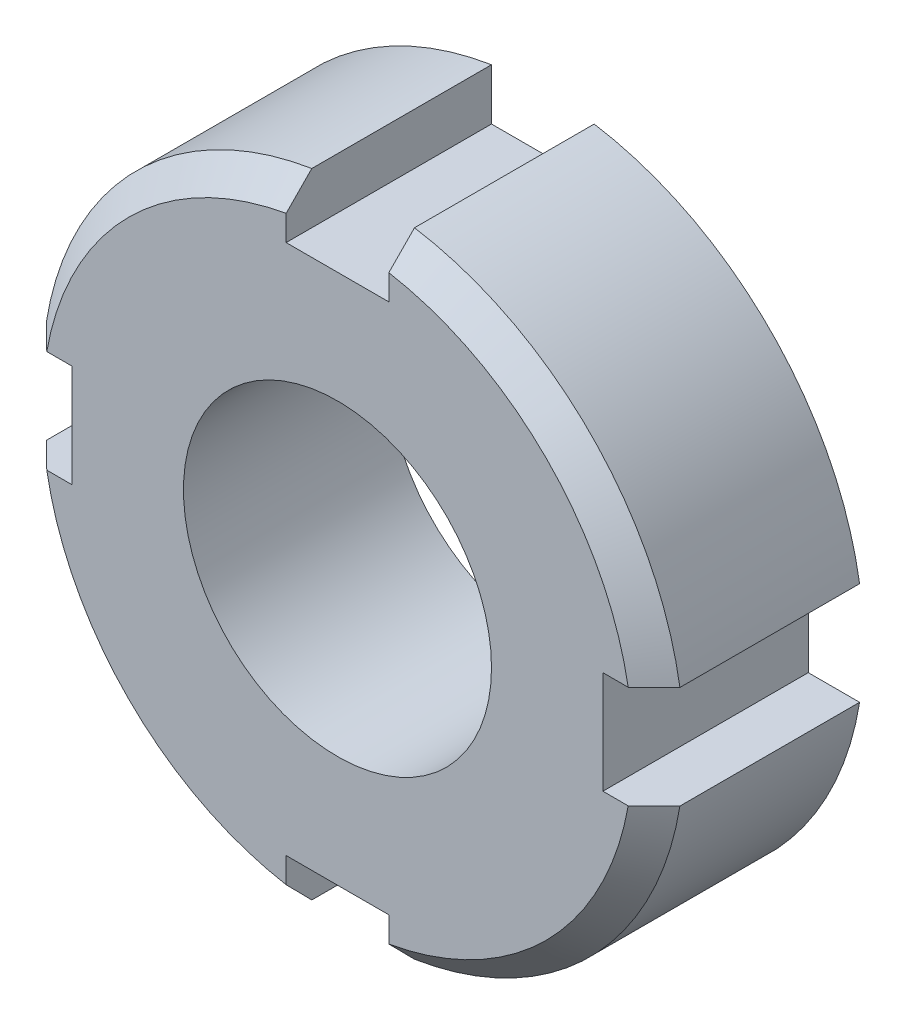
SolidWorks part; units mm, degrees
material "AISI 1020"
ref_plane "Front Plane" through (0, 0, 0) normal (0, 0, 1) x (1, 0, 0)
ref_plane "Top Plane" through (0, 0, 0) normal (0, 1, 0) x (1, 0, 0)
ref_plane "Right Plane" through (0, 0, 0) normal (1, 0, 0) x (0, 0, -1)
sketch "Sketch1" plane through (0, 0, 0) normal (0, 0, 1) x (1, 0, 0)
  circle A0 centre (0, 0) radius 12.5
  dimension "D1" = 25
extrude "Boss-Extrude1" add sketch "Sketch1" along normal blind 8
sketch "Sketch2" plane through (0, 0, 8) normal (0, 0, 1) x (1, 0, 0)
  line L0 (0, 14.2104) -> (0, -15.8191) construction
  line L1 (-2, 12.339) -> (-2, 10.339)
  line L2 (-2, 10.339) -> (2, 10.339)
  line L3 (2, 10.339) -> (2, 12.339)
  line L4 (12.339, 2) -> (10.339, 2)
  line L5 (10.339, 2) -> (10.339, -2)
  line L6 (10.339, -2) -> (12.339, -2)
  line L7 (2, -12.339) -> (2, -10.339)
  line L8 (2, -10.339) -> (-2, -10.339)
  line L9 (-2, -10.339) -> (-2, -12.339)
  line L10 (-12.339, -2) -> (-10.339, -2)
  line L11 (-10.339, -2) -> (-10.339, 2)
  line L12 (-10.339, 2) -> (-12.339, 2)
  circle A0 centre (0, 0) radius 12.5 construction
  arc A1 (-2, 12.339) -> (2, 12.339) centre (0, 0) cw
  arc A2 (12.339, 2) -> (12.339, -2) centre (0, 0) cw
  arc A3 (2, -12.339) -> (-2, -12.339) centre (0, 0) cw
  arc A4 (-12.339, -2) -> (-12.339, 2) centre (0, 0) cw
  point P7 (0, 10.339)
  point P26 (0, 0)
  dimension "D1" = 2
  dimension "D2" = 2
  dimension "D3" = 2
  dimension "D4" = 4
extrude "Cut-Extrude1" cut sketch "Sketch2" against normal through all
sketch "Sketch3" plane through (0, 0, 8) normal (0, 0, 1) x (1, 0, 0)
  circle A0 centre (0, 0) radius 6
  dimension "D1" = 12
extrude "Cut-Extrude2" cut sketch "Sketch3" against normal through all
cosmetic thread "Cosmetic Thread1" parameters "D2"=14
chamfer "Chamfer1" distance 1 angle 45 4 edges at (8.8388, -8.8388, 8) (-8.8388, -8.8388, 8) (-8.8388, 8.8388, 8) (8.8388, 8.8388, 8)
